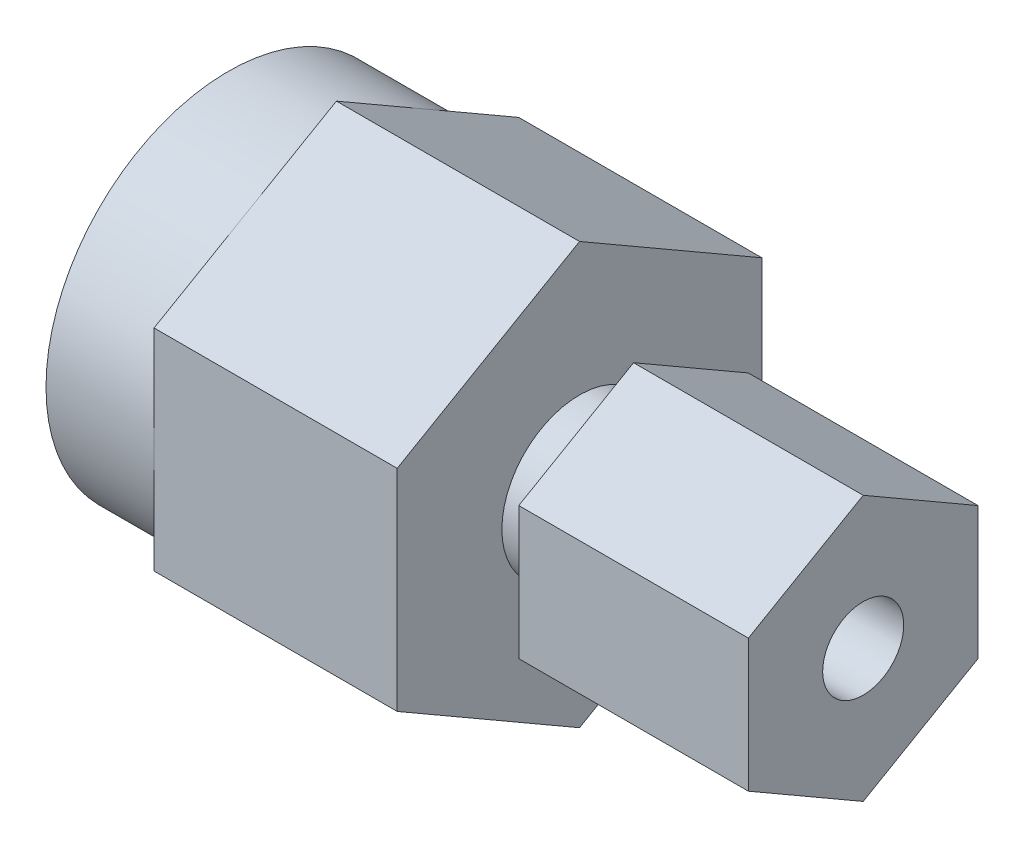
SolidWorks part; units mm, degrees
ref_plane "Front Plane" through (0, 0, 0) normal (0, 0, 1) x (1, 0, 0)
ref_plane "Top Plane" through (0, 0, 0) normal (0, 1, 0) x (1, 0, 0)
ref_plane "Right Plane" through (0, 0, 0) normal (1, 0, 0) x (0, 0, -1)
sketch "Skica1" plane through (0, 0, 0) normal (0, 0, 1) x (1, 0, 0)
  line L0 (0, 0) -> (27.0304, 0) construction
  line L1 (0, 9.5) -> (0, 13.5)
  line L2 (0, 13.5) -> (26, 13.5)
  line L3 (26, 13.5) -> (26, 5.75)
  line L4 (26, 5.75) -> (30, 5.75)
  line L5 (30, 5.75) -> (30, 10)
  line L6 (30, 10) -> (47, 10)
  line L7 (47, 10) -> (47, 3)
  line L8 (47, 3) -> (30.5, 3)
  line L9 (30.5, 3) -> (30.5, 2)
  line L10 (30.5, 2) -> (23, 2)
  line L11 (23, 2) -> (23, 3)
  line L12 (23, 3) -> (20, 3)
  line L13 (20, 3) -> (20, 9.5)
  line L14 (20, 9.5) -> (0, 9.5)
  point P5 (26.6669, 3)
  dimension "D1" = 27
  dimension "D2" = 19
  dimension "D3" = 11.5
  dimension "D4" = 20
  dimension "D5" = 6
  dimension "D6" = 4
  dimension "D7" = 6
  dimension "D8" = 20
  dimension "D9" = 47
  dimension "D10" = 3
  dimension "D11" = 26
  dimension "D12" = 17
  dimension "D13" = 16.5
revolve "Rotovat1" add sketch "Skica1" angle 360 about L0
sketch "Skica2" plane through (47, 0, 0) normal (1, 0, 0) x (0, 0, -1)
  line L1 (0, 9.815) -> (-8.5, 4.9075)
  line L2 (-8.5, 4.9075) -> (-8.5, -4.9075)
  line L3 (-8.5, -4.9075) -> (0, -9.815)
  line L4 (0, -9.815) -> (8.5, -4.9075)
  line L5 (8.5, -4.9075) -> (8.5, 4.9075)
  line L6 (8.5, 4.9075) -> (0, 9.815)
  circle A0 centre (0, 0) radius 8.5 construction
  circle A1 centre (0, 0) radius 11.3793
  dimension "D1" = 17
extrude "Odebrat vysunutím1" cut sketch "Skica2" against normal blind 18
sketch "Skica3" plane through (26, 0, 0) normal (1, 0, 0) x (0, 0, -1)
  line L1 (0, 15.5885) -> (-13.5, 7.7942)
  line L2 (-13.5, 7.7942) -> (-13.5, -7.7942)
  line L3 (-13.5, -7.7942) -> (0, -15.5885)
  line L4 (0, -15.5885) -> (13.5, -7.7942)
  line L5 (13.5, -7.7942) -> (13.5, 7.7942)
  line L6 (13.5, 7.7942) -> (0, 15.5885)
  circle A0 centre (0, 0) radius 12.7413
  circle A1 centre (0, 0) radius 13.5 construction
  dimension "D1" = 27
extrude "Přidat vysunutím1" add sketch "Skica3" against normal blind 18
